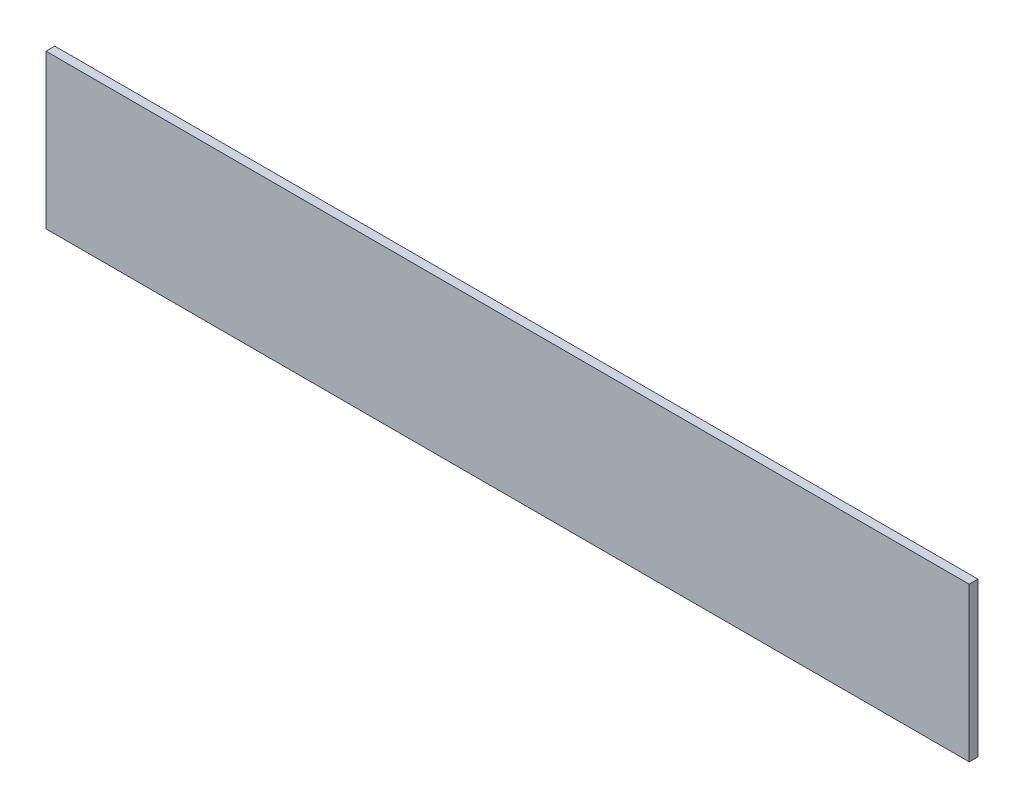
SolidWorks part; units mm, degrees
ref_plane "Front Plane" through (0, 0, 0) normal (0, 0, 1) x (1, 0, 0)
ref_plane "Top Plane" through (0, 0, 0) normal (0, 1, 0) x (1, 0, 0)
ref_plane "Right Plane" through (0, 0, 0) normal (1, 0, 0) x (0, 0, -1)
sketch "Sketch1" plane through (0, 0, 0) normal (0, 0, 1) x (1, 0, 0)
  line L1 (-65.8753, 33.2015) -> (200.8247, 33.2015)
  line L2 (-65.8753, 33.2015) -> (-65.8753, -11.2485)
  line L3 (-65.8753, -11.2485) -> (200.8247, -11.2485)
  line L4 (200.8247, 33.2015) -> (200.8247, -11.2485)
  dimension "D1" = 266.7
  dimension "D2" = 44.45
extrude "Boss-Extrude1" add sketch "Sketch1" along normal blind 2.54
